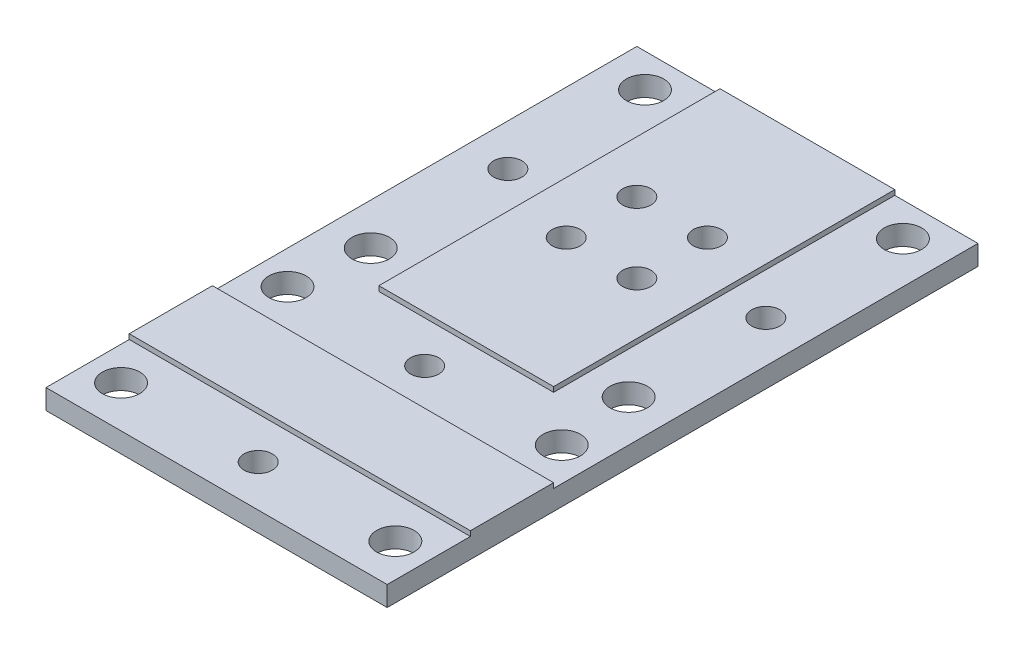
SolidWorks part; units mm, degrees
material "3.1355 (EN-AW 2024)"
ref_plane "Front" through (0, 0, 0) normal (0, 0, 1) x (1, 0, 0)
ref_plane "Top" through (0, 0, 0) normal (0, 1, 0) x (1, 0, 0)
ref_plane "Right" through (0, 0, 0) normal (1, 0, 0) x (0, 0, -1)
sketch "Эскиз1" plane through (0, 0, 0) normal (0, 1, 0) x (1, 0, 0)
  line L1 (0, 0) -> (41, 0)
  line L2 (0, 0) -> (0, 71)
  line L3 (0, 71) -> (41, 71)
  line L4 (41, 0) -> (41, 71)
  dimension "D1" = 41
  dimension "D2" = 71
extrude "Бобышка-Вытянуть1" add sketch "Эскиз1" along normal blind 3
sketch "Эскиз2" plane through (0, 3, 0) normal (0, 1, 0) x (1, 0, 0)
  line L0 (0, 10) -> (41, 10)
  line L1 (0, 71) -> (0, 0) construction
  line L2 (41, 0) -> (41, 71) construction
  line L3 (41, 10) -> (41, 0)
  line L4 (41, 0) -> (0, 0)
  line L5 (0, 0) -> (0, 10)
  line L6 (0, 71) -> (10, 71)
  line L7 (41, 71) -> (0, 71) construction
  line L8 (10, 71) -> (10, 30)
  line L10 (0, 30) -> (0, 71)
  line L11 (20.5, 71) -> (20.5, 0) construction
  line L12 (41, 30) -> (41, 71)
  line L14 (31, 71) -> (31, 30)
  line L15 (41, 71) -> (31, 71)
  line L16 (10, 30) -> (31, 30) construction
  line L17 (10, 30) -> (10, 0) construction
  line L18 (10, 15) -> (0, 15) construction
  line L19 (0, 30) -> (0, 20)
  line L20 (31, 30) -> (10, 30)
  line L21 (41, 20) -> (41, 30)
  line L22 (0, 20) -> (41, 20)
  dimension "D1" = 10
  dimension "D2" = 10
  dimension "D3" = 41
extrude "Вырез-Вытянуть1" cut sketch "Эскиз2" against normal blind 0.6
hole_wizard "Отверстие с зазором M41" positions "Эскиз3" profile "Эскиз4" hole size "M4" standard "Ansi Metric" end condition through all
sketch "Эскиз3" plane through (24.3175, 3, -29.9708) normal (0, 1, 0) x (1, 0, 0)
  point P0 (-20.2975, -24.9708)
  point P3 (12.6625, -24.9708)
  point P6 (12.6625, -4.9708)
  point P9 (-20.2975, -4.9708)
  point P12 (-19.3175, 4.0492)
  point P15 (11.6825, 4.0492)
  point P18 (11.6825, 37.0092)
  point P21 (-19.3175, 37.0092)
sketch "Эскиз4" plane through (4.02, 3, -5) normal (1, 0, 0) x (0, 0, 1)
  line L0 (0, 0) -> (0, 3)
  line L1 (0, 3) -> (2.25, 3)
  line L2 (2.25, 3) -> (2.25, 0)
  line L3 (2.25, 0) -> (0, 0)
  line L4 (0, -6.35) -> (0, 107.95) construction
  dimension "Диаметр сквозного отверстия" = 4.5
  dimension "Глубина сквозного отверстия" = 3
hole_wizard "Отверстие с зазором M31" positions "Эскиз5" profile "Эскиз6" hole size "M3" standard "Ansi Metric" end condition through all
sketch "Эскиз5" plane through (24.3175, 3, -29.9708) normal (0, 1, 0) x (1, 0, 0)
  point P0 (-3.8175, -24.9708)
  point P3 (-3.8175, -4.9708)
  point P6 (-19.3175, 20.5292)
  point P9 (11.6825, 20.5292)
sketch "Эскиз6" plane through (20.5, 3, -5) normal (1, 0, 0) x (0, 0, 1)
  line L0 (0, 0) -> (0, 3)
  line L1 (0, 3) -> (1.7, 3)
  line L2 (1.7, 3) -> (1.7, 0)
  line L3 (1.7, 0) -> (0, 0)
  line L4 (0, -6.35) -> (0, 107.95) construction
  dimension "Диаметр сквозного отверстия" = 3.4
  dimension "Глубина сквозного отверстия" = 3
sketch "Эскиз7" plane through (0, 3, 0) normal (0, 1, 0) x (1, 0, 0)
  line L0 (20.5, 30) -> (20.5, 71) construction
  line L1 (31, 30) -> (10, 30) construction
  line L2 (31, 71) -> (10, 71) construction
  line L3 (20.5, 50.5) -> (16.2574, 54.7426) construction
  line L4 (31, 30) -> (10, 30) construction
  line L5 (20.5, 50.5) -> (24.7426, 54.7426) construction
  line L6 (20.5, 50.5) -> (24.7426, 46.2574) construction
  line L7 (20.5, 50.5) -> (16.2574, 46.2574) construction
  circle A0 centre (20.5, 50.5) radius 6 construction
  point P17 (20.5, 50.5)
  dimension "D1" = 12
  dimension "D2" = 45
  dimension "D3" = 4
hole_wizard "Отверстие с зазором M32" positions "Эскиз9" profile "Эскиз8" hole size "M3" standard "Ansi Metric" end condition through all
sketch "Эскиз9" plane through (0, 3, 0) normal (0, 1, 0) x (1, 0, 0)
  point P0 (16.2574, 46.2574)
  point P3 (16.2574, 54.7426)
  point P6 (24.7426, 54.7426)
  point P9 (24.7426, 46.2574)
sketch "Эскиз8" plane through (16.2574, 3, -46.2574) normal (1, 0, 0) x (0, 0, 1)
  line L0 (0, 0) -> (0, 3)
  line L1 (0, 3) -> (1.7, 3)
  line L2 (1.7, 3) -> (1.7, 0)
  line L5 (1.7, 0) -> (0, 0)
  line L11 (0, -6.35) -> (0, 107.95) construction
  dimension "Диаметр сквозного отверстия" = 3.4
  dimension "Глубина сквозного отверстия" = 3
equation "\"D2@Эскиз1\"=10+10+10+41"
